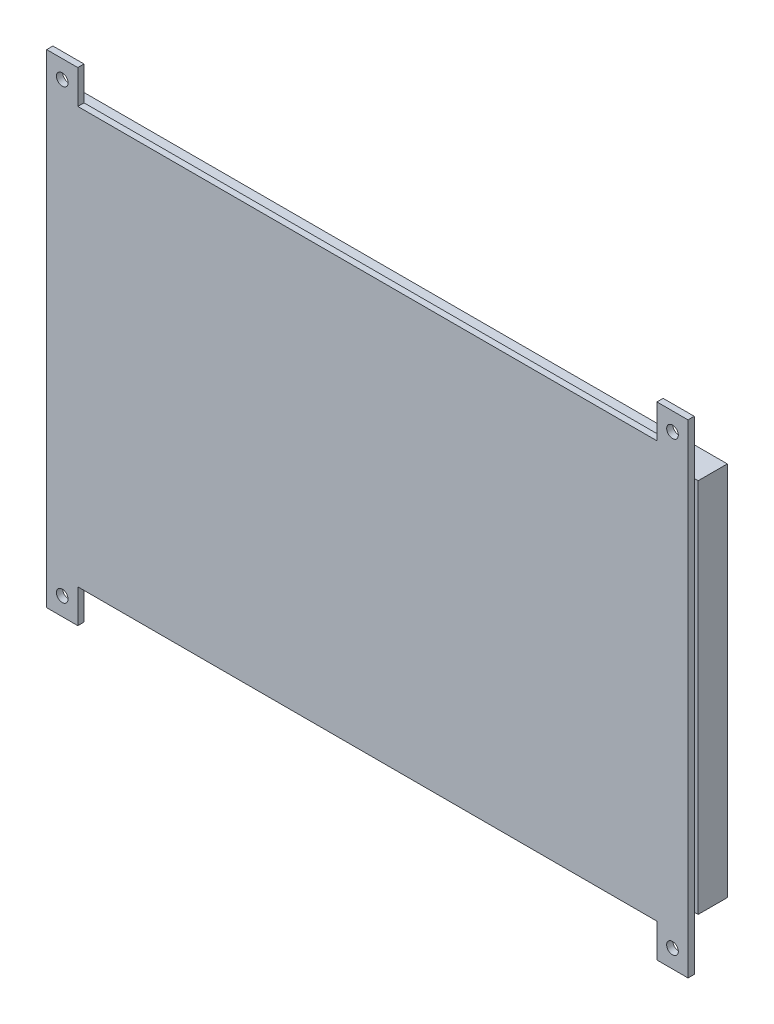
SolidWorks part; units mm, degrees
ref_plane "Front Plane" through (0, 0, 0) normal (0, 0, 1) x (1, 0, 0)
ref_plane "Top Plane" through (0, 0, 0) normal (0, 1, 0) x (1, 0, 0)
ref_plane "Right Plane" through (0, 0, 0) normal (1, 0, 0) x (0, 0, -1)
sketch "Sketch1" plane through (0, 0, 0) normal (0, 0, 1) x (1, 0, 0)
  line L0 (0, 44.3447) -> (0, -15.9157) construction
  line L1 (-74.45, -53.48) -> (74.45, -53.48)
  line L2 (-82.45, -53.48) -> (-82.45, 53.48)
  line L3 (-74.45, 53.48) -> (74.45, 53.48)
  line L4 (82.45, -53.48) -> (82.45, 53.48)
  line L5 (-82.45, -53.48) -> (82.45, 53.48) construction
  line L6 (-82.45, 53.48) -> (82.45, -53.48) construction
  line L7 (0, -44.7868) -> (0, 44.7868) construction
  line L8 (55, 0) -> (-55, 0) construction
  line L9 (-74.45, -53.48) -> (-74.45, -62.135)
  line L11 (82.45, 53.48) -> (82.45, 62.135)
  line L12 (82.45, 62.135) -> (74.45, 62.135)
  line L13 (74.45, 53.48) -> (74.45, 62.135)
  line L15 (-82.45, 53.48) -> (-82.45, 62.135)
  line L16 (-82.45, 62.135) -> (-74.45, 62.135)
  line L17 (-74.45, 53.48) -> (-74.45, 62.135)
  line L18 (-82.45, -53.48) -> (-82.45, -62.135)
  line L19 (82.45, -53.48) -> (82.45, -62.135)
  line L20 (74.45, -53.48) -> (74.45, -62.135)
  line L21 (-82.45, -62.135) -> (-74.45, -62.135)
  line L22 (82.45, -62.135) -> (74.45, -62.135)
  circle A0 centre (78.45, 57.48) radius 1.5
  circle A1 centre (-78.45, 57.48) radius 1.5
  circle A2 centre (-78.45, -57.48) radius 1.5
  circle A3 centre (78.45, -57.48) radius 1.5
  point P0 (0, 0)
  point P22 (-74.45, 57.8075)
  dimension "D7" = 3
  dimension "D8" = 3
  dimension "D1" = 164.9
  dimension "D2" = 106.96
  dimension "D3" = 156.9
  dimension "D4" = 57.48
  dimension "D5" = 148.9
  dimension "D6" = 62.135
extrude "Boss-Extrude1" add sketch "Sketch1" along normal blind 1.6
sketch "Sketch2" plane through (0, 0, 0) normal (0, 0, -1) x (-1, 0, 0)
  line L0 (-83.45, 48.2869) -> (83.45, 48.2869)
  line L1 (-78.45, 43.2869) -> (78.45, 43.2869)
  line L2 (-78.45, 43.2869) -> (-78.45, -43.2869)
  line L3 (-78.45, -43.2869) -> (78.45, -43.2869)
  line L4 (78.45, 43.2869) -> (78.45, -43.2869)
  line L5 (-78.45, 43.2869) -> (78.45, -43.2869) construction
  line L6 (-78.45, -43.2869) -> (78.45, 43.2869) construction
  line L7 (83.45, 48.2869) -> (83.45, -48.2869)
  line L8 (-83.45, -48.2869) -> (83.45, -48.2869)
  line L9 (-83.45, 48.2869) -> (-83.45, -48.2869)
  point P0 (0, 0)
  dimension "D1" = 179.2
  dimension "D2" = 156.9
  dimension "D3" = 5
extrude "Boss-Extrude2" add sketch "Sketch2" along normal blind 7.5
sketch "Sketch3" plane through (0, 0, 0) normal (0, 0, -1) x (-1, 0, 0)
  line L1 (-78.45, -43.2869) -> (78.45, -43.2869)
  line L2 (-78.45, -43.2869) -> (-78.45, 43.2869)
  line L3 (-78.45, 43.2869) -> (78.45, 43.2869)
  line L4 (78.45, -43.2869) -> (78.45, 43.2869)
  line L5 (-78.45, -43.2869) -> (78.45, 43.2869) construction
  line L6 (-78.45, 43.2869) -> (78.45, -43.2869) construction
  point P0 (0, 0)
extrude "Boss-Extrude3" add sketch "Sketch3" along normal blind 4
